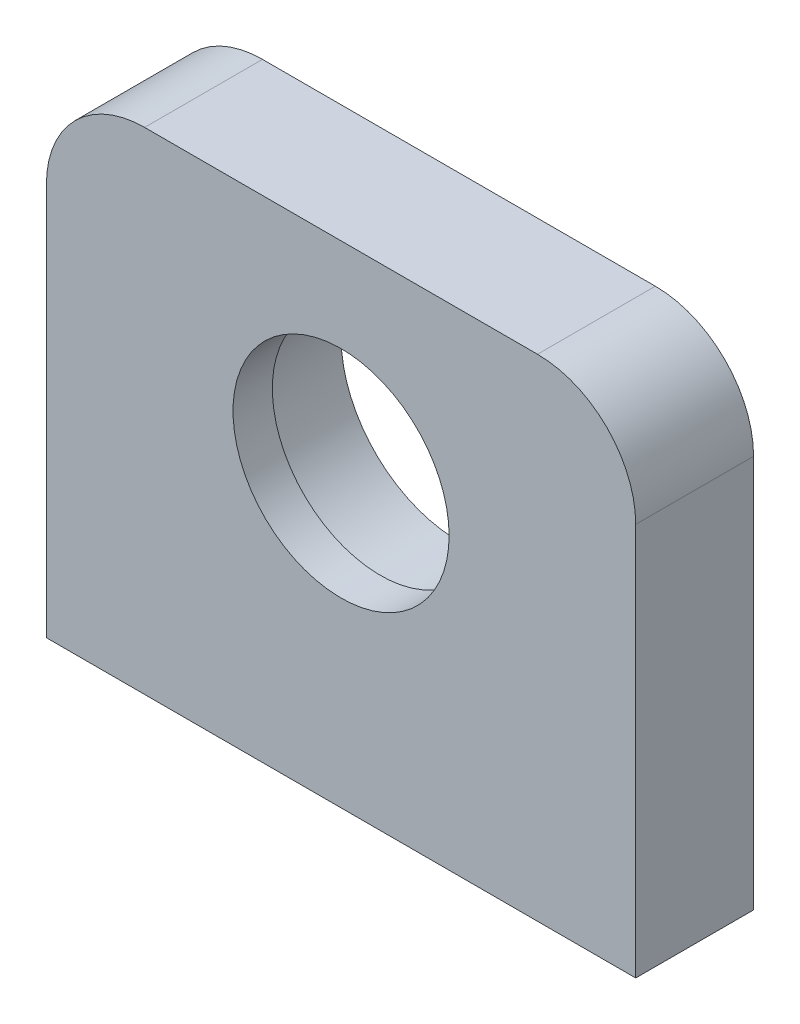
SolidWorks part; units mm, degrees
material "HDPE-green"
ref_plane "Front Plane" through (0, 0, 0) normal (0, 0, 1) x (1, 0, 0)
ref_plane "Top Plane" through (0, 0, 0) normal (0, 1, 0) x (1, 0, 0)
ref_plane "Right Plane" through (0, 0, 0) normal (1, 0, 0) x (0, 0, -1)
sketch "Sketch1" plane through (0, 0, 0) normal (0, 0, 1) x (1, 0, 0)
  line L1 (-30, 25) -> (30, 25)
  line L2 (-30, 25) -> (-30, -25)
  line L3 (-30, -25) -> (30, -25)
  line L4 (30, 25) -> (30, -25)
  line L5 (-30, 25) -> (30, -25) construction
  line L6 (-30, -25) -> (30, 25) construction
  point P0 (0, 0)
  dimension "D1" = 60
  dimension "D2" = 50
extrude "Boss-Extrude1" add sketch "Sketch1" along normal blind 12
sketch "Sketch2" plane through (0, 0, 12) normal (0, 0, 1) x (1, 0, 0)
  line L3 (-30, -25) -> (30, -25) construction
  circle A0 centre (0, 4.5) radius 11
  dimension "D1" = 22
  dimension "D2" = 29.5
extrude "Cut-Extrude1" cut sketch "Sketch2" against normal blind 4
sketch "Sketch6" plane through (0, 0, 8) normal (0, 0, 1) x (1, 0, 0)
  circle A0 centre (0, 4.5) radius 12
  dimension "D1" = 24
extrude "Cut-Extrude5" cut sketch "Sketch6" against normal up to next
sketch "Sketch9" plane through (33.3552, 100.1109, 0) normal (0, 0, -1) x (-1, 0, 0)
  line L0 (9.3552, -113.1109) -> (17.3552, -113.1109) construction
  line L1 (9.3552, -111.1109) -> (17.3552, -111.1109)
  line L2 (9.3552, -115.1109) -> (17.3552, -115.1109)
  line L3 (63.3552, -125.1109) -> (3.3552, -125.1109) construction
  line L4 (3.3552, -125.1109) -> (3.3552, -75.1109) construction
  arc A0 (9.3552, -111.1109) -> (9.3552, -115.1109) centre (9.3552, -113.1109) ccw
  arc A1 (17.3552, -115.1109) -> (17.3552, -111.1109) centre (17.3552, -113.1109) ccw
  point P2 (13.3552, -113.1109)
  dimension "D1" = 8
  dimension "D2" = 2
  dimension "D3" = 12
  dimension "D4" = 10
extrude "Cut-Extrude7" cut sketch "Sketch9" against normal blind 8
sketch "Sketch11" plane through (33.3552, 100.1109, 0) normal (0, 0, -1) x (-1, 0, 0)
  line L0 (13.3552, -108.1109) -> (13.3552, -132.0254) construction
  line L1 (15.8552, -108.1109) -> (15.8552, -132.0254)
  line L2 (10.8552, -108.1109) -> (10.8552, -132.0254)
  line L3 (3.3552, -125.1109) -> (3.3552, -75.1109) construction
  line L4 (63.3552, -125.1109) -> (3.3552, -125.1109) construction
  arc A0 (15.8552, -108.1109) -> (10.8552, -108.1109) centre (13.3552, -108.1109) ccw
  arc A1 (10.8552, -132.0254) -> (15.8552, -132.0254) centre (13.3552, -132.0254) ccw
  point P2 (13.3552, -120.0682)
  dimension "D1" = 10
  dimension "D2" = 2.5
  dimension "D3" = 17
extrude "Cut-Extrude8" cut sketch "Sketch11" against normal blind 6.5
mirror "Mirror1" about plane through (0, 0, 0) normal (1, 0, 0) of "Cut-Extrude8", "Cut-Extrude7"
fillet "Fillet1" radius 10 2 edges at (-30, 25, 6) (30, 25, 6)
